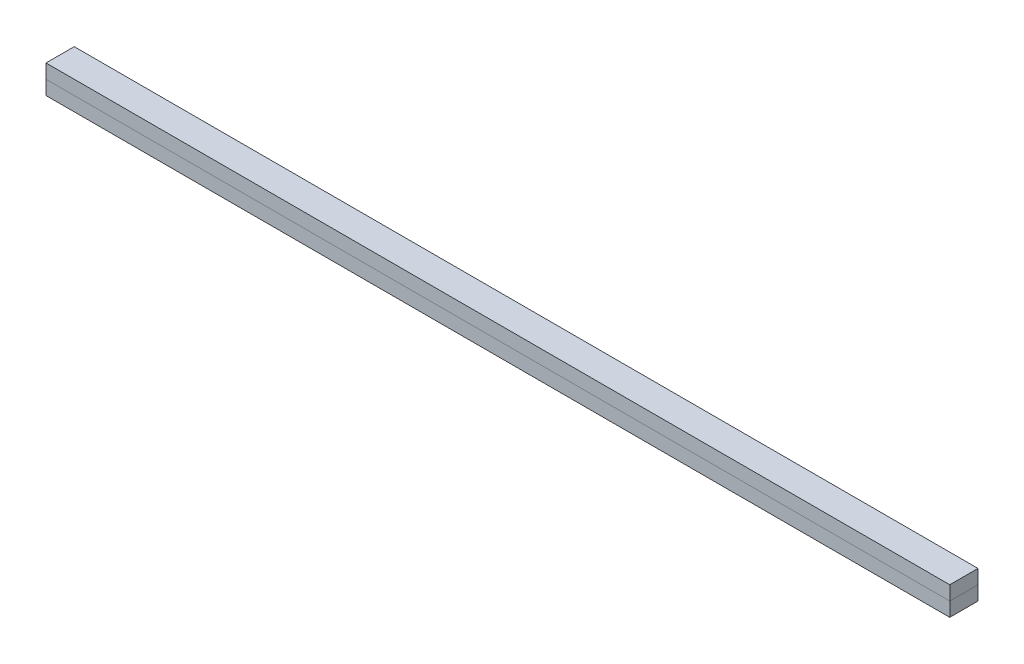
SolidWorks part; units mm, degrees
ref_plane "Front Plane" through (0, 0, 0) normal (0, 0, 1) x (1, 0, 0)
ref_plane "Top Plane" through (0, 0, 0) normal (0, 1, 0) x (1, 0, 0)
ref_plane "Right Plane" through (0, 0, 0) normal (1, 0, 0) x (0, 0, -1)
other "Configuration Table"
sketch "Sketch1" plane through (0, 0, 0) normal (1, 0, 0) x (0, 0, -1)
  line L0 (55, 0) -> (-55, 0) construction
  line L1 (-50, 0) -> (50, 0)
  line L2 (-50, 0) -> (-50, -50)
  line L3 (-50, -50) -> (50, -50)
  line L4 (50, 0) -> (50, -50)
  dimension "D1" = 50
  dimension "D2" = 100
extrude "Extrude1" add sketch "Sketch1" against normal blind 3200
mirror "Mirror1" about plane through (0, 0, 0) normal (0, 1, 0) of "Extrude1"
sketch "Sketch2" plane through (-3200, 0, 0) normal (-1, 0, 0) x (0, 0, 1)
  line L0 (-76.0494, 0) -> (87.1559, 0)
split line "Split Line1"
